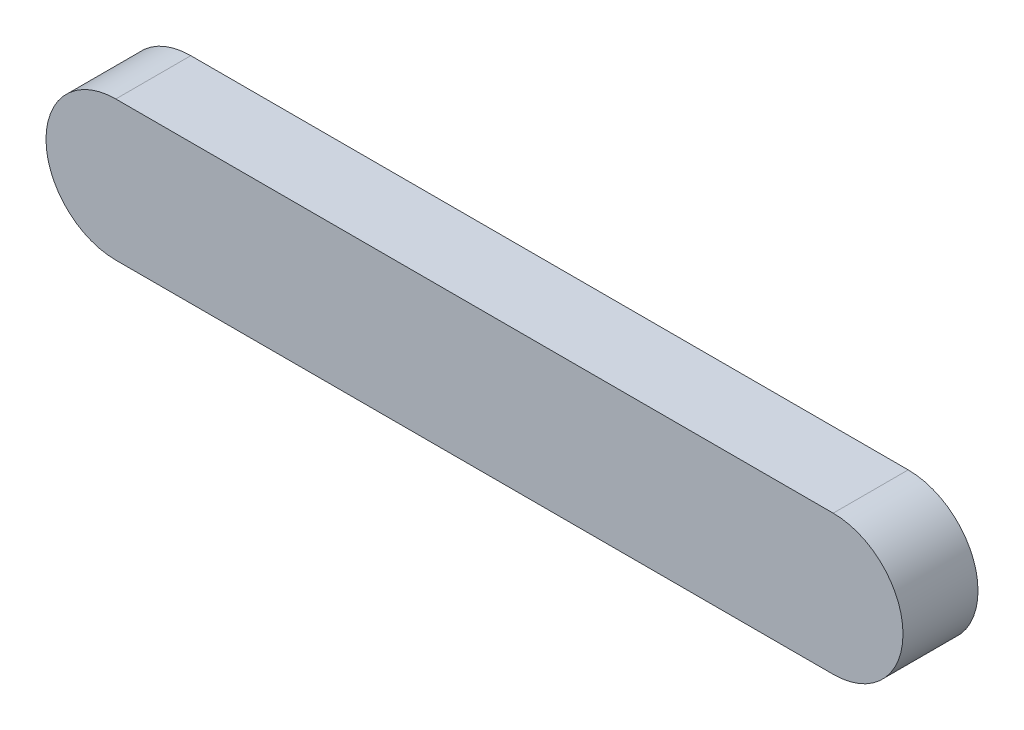
SolidWorks part; units mm, degrees
ref_plane "Front Plane" through (0, 0, 0) normal (0, 0, 1) x (1, 0, 0)
ref_plane "Top Plane" through (0, 0, 0) normal (0, 1, 0) x (1, 0, 0)
ref_plane "Right Plane" through (0, 0, 0) normal (1, 0, 0) x (0, 0, -1)
sketch "Sketch1" plane through (0, 0, 0) normal (0, 0, 1) x (1, 0, 0)
  line L0 (41.1169, 0) -> (-54.5339, 0) construction
  line L1 (41.1169, -9.3054) -> (-54.5339, -9.3054)
  line L2 (41.1169, 9.3054) -> (-54.5339, 9.3054)
  arc A0 (41.1169, -9.3054) -> (41.1169, 9.3054) centre (41.1169, 0) ccw
  arc A1 (-54.5339, 9.3054) -> (-54.5339, -9.3054) centre (-54.5339, 0) ccw
  point P3 (-6.7085, 0)
extrude "Boss-Extrude1" add sketch "Sketch1" along normal blind 10
